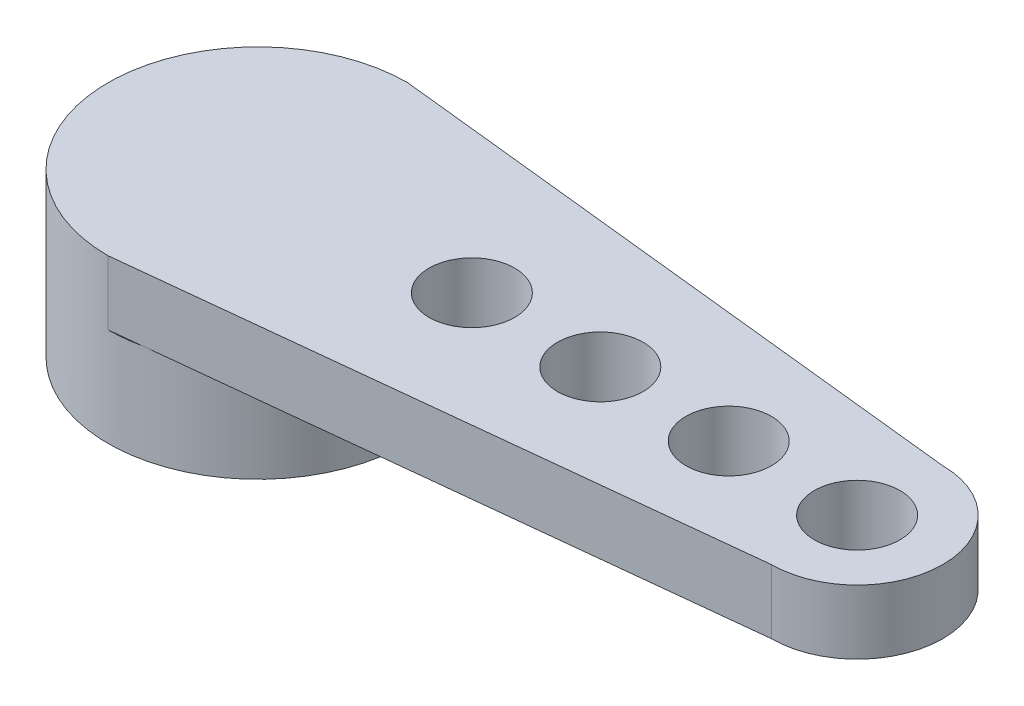
SolidWorks part; units mm, degrees
material "ABS"
ref_plane "Front Plane" through (0, 0, 0) normal (0, 0, 1) x (1, 0, 0)
ref_plane "Top Plane" through (0, 0, 0) normal (0, 1, 0) x (1, 0, 0)
ref_plane "Right Plane" through (0, 0, 0) normal (1, 0, 0) x (0, 0, -1)
sketch "Sketch1" plane through (0, 0, 0) normal (0, 1, 0) x (1, 0, 0)
  line L0 (0, 0) -> (14, 0) construction
  line L1 (0, 3.5) -> (14, 2)
  line L2 (0, -3.5) -> (14, -2)
  arc A0 (0, 3.5) -> (0, -3.5) centre (0, 0) ccw
  arc A1 (14, -2) -> (14, 2) centre (14, 0) ccw
  dimension "D1" = 7
  dimension "D2" = 4
  dimension "D3" = 14
extrude "Boss-Extrude1" add sketch "Sketch1" along normal blind 1.5
sketch "Sketch2" plane through (0, 0, 0) normal (0, -1, 0) x (1, 0, 0)
  circle A0 centre (0, 0) radius 2.4
  circle A1 centre (0, 0) radius 3.5
  dimension "D1" = 7
  dimension "D2" = 4.8
extrude "Boss-Extrude2" add sketch "Sketch2" along normal blind 2.3
sketch "Sketch3" plane through (0, 1.5, 0) normal (0, 1, 0) x (1, 0, 0)
  line L0 (0, 0) -> (16, 0) construction
  arc A1 (14, -2) -> (14, 2) centre (14, 0) ccw construction
  circle A2 centre (14, 0) radius 1
  circle A8 centre (11, 0) radius 1
  circle A9 centre (8, 0) radius 1
  circle A10 centre (5, 0) radius 1
  dimension "D1" = 2
  dimension "D2" = 2
  dimension "D3" = 4
extrude "Cut-Extrude2" cut sketch "Sketch3" against normal through all
